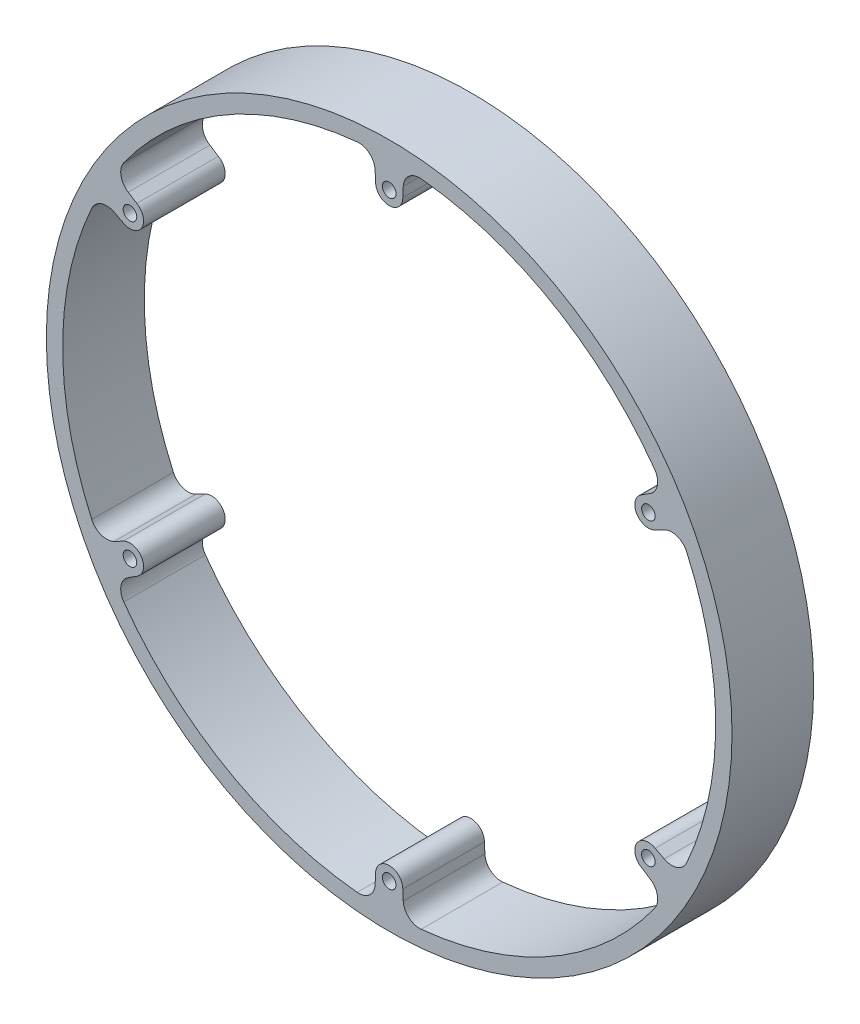
SolidWorks part; units mm, degrees
ref_plane "前视基准面" through (0, 0, 0) normal (0, 0, 1) x (1, 0, 0)
ref_plane "上视基准面" through (0, 0, 0) normal (0, 1, 0) x (1, 0, 0)
ref_plane "右视基准面" through (0, 0, 0) normal (1, 0, 0) x (0, 0, -1)
sketch "草图1" plane through (0, 0, 0) normal (0, 0, 1) x (1, 0, 0)
  line L0 (-2.5, 55) -> (-2.7245, 59.9381)
  line L1 (0, 55) -> (-47.6314, 27.5) construction
  line L2 (-47.6314, 27.5) -> (-47.6314, -27.5) construction
  line L3 (-47.6314, -27.5) -> (0, -55) construction
  line L4 (0, -55) -> (47.6314, -27.5) construction
  line L5 (47.6314, -27.5) -> (47.6314, 27.5) construction
  line L6 (47.6314, 27.5) -> (0, 55) construction
  line L7 (2.5, 55) -> (2.7245, 59.9381)
  line L8 (46.3814, 29.6651) -> (50.5457, 32.3285)
  line L9 (48.8814, 25.3349) -> (53.2702, 27.6096)
  line L10 (48.8814, -25.3349) -> (53.2702, -27.6096)
  line L11 (46.3814, -29.6651) -> (50.5457, -32.3285)
  line L12 (2.5, -55) -> (2.7245, -59.9381)
  line L13 (-2.5, -55) -> (-2.7245, -59.9381)
  line L14 (-46.3814, -29.6651) -> (-50.5457, -32.3285)
  line L15 (-48.8814, -25.3349) -> (-53.2702, -27.6096)
  line L16 (-48.8814, 25.3349) -> (-53.2702, 27.6096)
  line L17 (-46.3814, 29.6651) -> (-50.5457, 32.3285)
  circle A0 centre (0, 0) radius 63
  arc A1 (-2.7245, 59.9381) -> (-50.5457, 32.3285) centre (0, 0) ccw
  circle A2 centre (0, 0) radius 47.6314 construction
  circle A3 centre (0, 55) radius 1.25
  arc A9 (-2.5, 55) -> (2.5, 55) centre (0, 55) ccw
  arc A15 (2.5, 55) -> (-2.5, 55) centre (0, 55) ccw construction
  circle A16 centre (47.6314, 27.5) radius 1.25
  arc A17 (46.3814, 29.6651) -> (48.8814, 25.3349) centre (47.6314, 27.5) ccw
  circle A18 centre (47.6314, -27.5) radius 1.25
  arc A19 (48.8814, -25.3349) -> (46.3814, -29.6651) centre (47.6314, -27.5) ccw
  circle A20 centre (0, -55) radius 1.25
  arc A21 (2.5, -55) -> (-2.5, -55) centre (0, -55) ccw
  circle A22 centre (-47.6314, -27.5) radius 1.25
  arc A23 (-46.3814, -29.6651) -> (-48.8814, -25.3349) centre (-47.6314, -27.5) ccw
  circle A24 centre (-47.6314, 27.5) radius 1.25
  arc A25 (-48.8814, 25.3349) -> (-46.3814, 29.6651) centre (-47.6314, 27.5) ccw
  arc A26 (2.7245, 59.9381) -> (-2.7245, 59.9381) centre (0, 0) ccw construction
  arc A27 (50.5457, 32.3285) -> (2.7245, 59.9381) centre (0, 0) ccw
  arc A28 (53.2702, 27.6096) -> (50.5457, 32.3285) centre (0, 0) ccw construction
  arc A29 (53.2702, -27.6096) -> (53.2702, 27.6096) centre (0, 0) ccw
  arc A30 (50.5457, -32.3285) -> (53.2702, -27.6096) centre (0, 0) ccw construction
  arc A31 (2.7245, -59.9381) -> (50.5457, -32.3285) centre (0, 0) ccw
  arc A32 (-2.7245, -59.9381) -> (2.7245, -59.9381) centre (0, 0) ccw construction
  arc A33 (-50.5457, -32.3285) -> (-2.7245, -59.9381) centre (0, 0) ccw
  arc A34 (-53.2702, -27.6096) -> (-50.5457, -32.3285) centre (0, 0) ccw construction
  arc A35 (-53.2702, 27.6096) -> (-53.2702, -27.6096) centre (0, 0) ccw
  arc A36 (-50.5457, 32.3285) -> (-53.2702, 27.6096) centre (0, 0) ccw construction
  point P25 (0, 0)
  point P36 (0, 0)
  point P51 (0, 0)
  dimension "D1" = 126
  dimension "D2" = 3
  dimension "D5" = 2.5
  dimension "D6" = 5
  dimension "D3" = 110
  dimension "D4" = 6
extrude "凸台-拉伸1" add sketch "草图1" along normal blind 15
fillet "圆角1" radius 3 12 edges at (53.2702, 27.6096, 7.5) (50.5457, 32.3285, 7.5) (50.5457, -32.3285, 7.5) (53.2702, -27.6096, 7.5) (-2.7245, -59.9381, 7.5) (2.7245, -59.9381, 7.5) (-53.2702, -27.6096, 7.5) (-50.5457, -32.3285, 7.5) (-50.5457, 32.3285, 7.5) (-53.2702, 27.6096, 7.5) (-2.7245, 59.9381, 7.5) (2.7245, 59.9381, 7.5)
